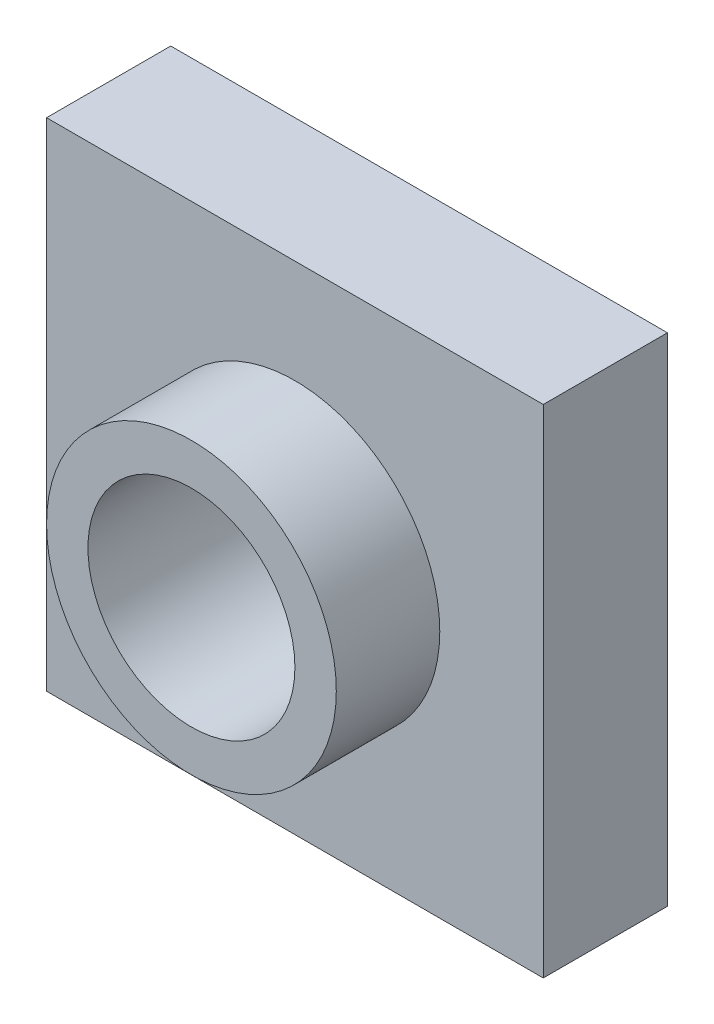
SolidWorks part; units mm, degrees
ref_plane "Front Plane" through (0, 0, 0) normal (0, 0, 1) x (1, 0, 0)
ref_plane "Top Plane" through (0, 0, 0) normal (0, 1, 0) x (1, 0, 0)
ref_plane "Right Plane" through (0, 0, 0) normal (1, 0, 0) x (0, 0, -1)
other "Configuration Table"
sketch "Sketch2" plane through (0, 0, 0) normal (0, 0, 1) x (1, 0, 0)
  line L1 (0, 0) -> (120, 0)
  line L2 (0, 0) -> (0, 120)
  line L3 (0, 120) -> (120, 120)
  line L4 (120, 0) -> (120, 120)
  dimension "D1" = 120
  dimension "D2" = 120
extrude "Boss-Extrude1" add sketch "Sketch2" along normal blind 30
sketch "Sketch4" plane through (0, 0, 30) normal (0, 0, 1) x (1, 0, 0)
  line L0 (120, 120) -> (0, 120) construction
  line L1 (0, 120) -> (0, 0) construction
  circle A0 centre (60, 60) radius 35
  dimension "D1" = 60
  dimension "D3" = 70
  dimension "D2" = 60
extrude "Boss-Extrude2" add sketch "Sketch4" along normal blind 25
sketch "Sketch6" plane through (0, 0, 55) normal (0, 0, 1) x (1, 0, 0)
  circle A0 centre (60, 60) radius 25
  dimension "D1" = 50
extrude "Cut-Extrude1" cut sketch "Sketch6" against normal through all
